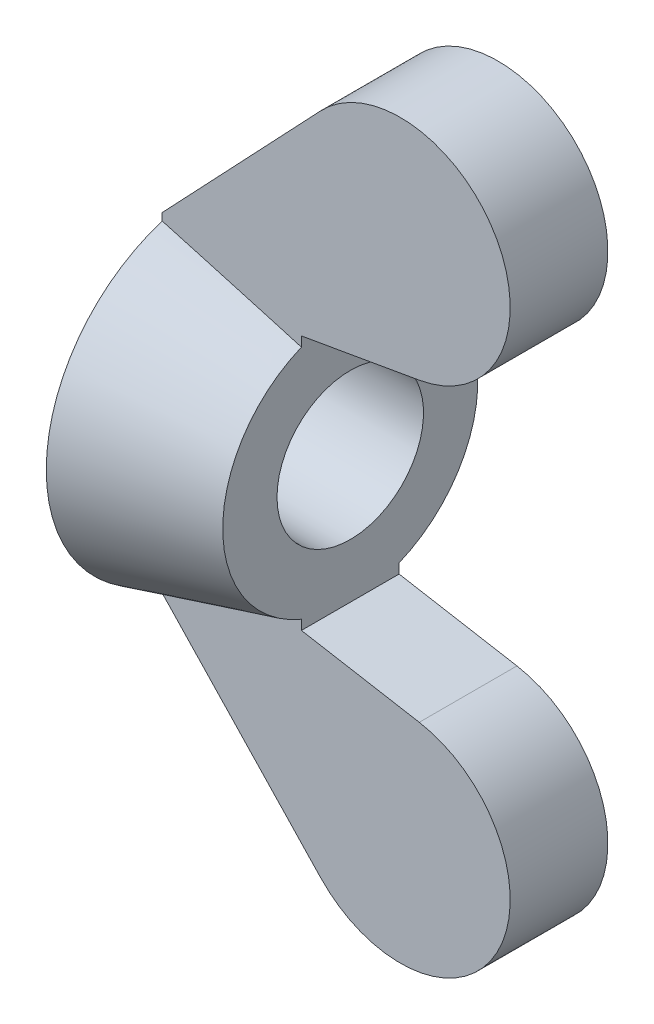
SolidWorks part; units mm, degrees
ref_plane "Front Plane" through (0, 0, 0) normal (0, 0, 1) x (1, 0, 0)
ref_plane "Top Plane" through (0, 0, 0) normal (0, 1, 0) x (1, 0, 0)
ref_plane "Right Plane" through (0, 0, 0) normal (1, 0, 0) x (0, 0, -1)
sketch "Sketch2" plane through (0, 0, 0) normal (0, 1, 0) x (1, 0, 0)
  line L0 (0, 2) -> (0, 4.5)
  line L1 (0, -4.95) -> (0, 4.95) construction
  line L2 (0, 4.5) -> (3.8, 3.4818)
  line L3 (3.8, 3.4818) -> (3.8, 2)
  line L5 (0, 2) -> (3.8, 2)
  line L6 (-5.225, 0) -> (5.225, 0) construction
  line L7 (0, 0) -> (8.4032, 0) construction
  dimension "D2" = 3.8
  dimension "D3" = 75
  dimension "D1" = 4.5
  dimension "D4" = 2
revolve "Revolve1" add sketch "Sketch2" angle 360 about L7
sketch "Sketch3" plane through (0, 0, 0) normal (0, 0, 1) x (1, 0, 0)
  line L0 (0, 4.5) -> (4.3219, 9.063)
  line L1 (0, -4.95) -> (0, 4.95) construction
  line L2 (7.0172, 4.0449) -> (3.8, 3.4818)
  line L3 (3.8, 3.4818) -> (0, 4.5) construction
  line L4 (0, 4.5) -> (0, 2)
  line L5 (0, 2) -> (3.8, 2)
  line L6 (3.8, -3.4818) -> (3.8, 3.4818) construction
  line L7 (3.8, 2) -> (3.8, 3.4818)
  line L9 (9.5, -0.3477) -> (9.5, 6.5965) construction
  line L10 (-2.6463, 10) -> (10.4057, 10) construction
  line L11 (4.95, 0) -> (-4.95, 0) construction
  arc A0 (4.3219, 9.063) -> (7.0172, 4.0449) centre (6.5, 7) cw
  dimension "D3" = 3
  dimension "D1" = 9.5
  dimension "D2" = 10
extrude "Boss-Extrude1" add sketch "Sketch3" along normal mid plane 2.6667
mirror "Mirror1" about plane through (0, 0, 0) normal (0, 1, 0) of "Boss-Extrude1"
equation "\"dk\"= 9"
equation "\"e\"= 20"
equation "\"D\"= 4"
equation "\"h\"= 9.5"
equation "\"m\"= 3.8"
equation "\"D1@Sketch2\"= \"dk\" / 2"
equation "\"D2@Sketch2\"= \"m\""
equation "\"D4@Sketch2\"=\"D\" / 2"
equation "\"D1@Sketch3\"= \"h\""
equation "\"D2@Sketch3\"= \"e\" / 2"
equation "\"D1@Boss-Extrude1\"=2 / 3 * \"D\""
